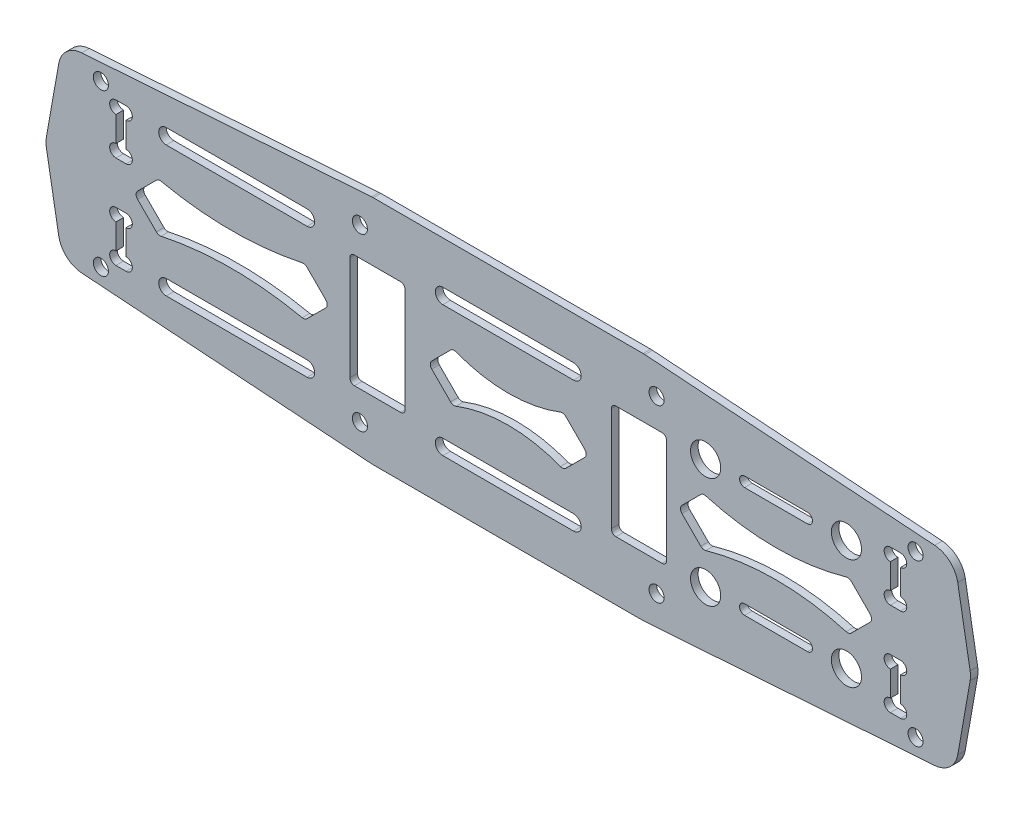
SolidWorks part; units mm, degrees
ref_plane "Front Plane" through (0, 0, 0) normal (0, 0, 1) x (1, 0, 0)
ref_plane "Top Plane" through (0, 0, 0) normal (0, 1, 0) x (1, 0, 0)
ref_plane "Right Plane" through (0, 0, 0) normal (1, 0, 0) x (0, 0, -1)
sketch "Sketch1" plane through (0, 0, 0) normal (0, 0, 1) x (1, 0, 0)
  line L0 (11.4571, 4.4571) -> (15.2071, 0.7071)
  line L1 (15.2071, -0.7071) -> (11.4571, -4.4571)
  line L2 (-11.4571, -4.4571) -> (-15.2071, -0.7071)
  line L3 (-15.2071, 0.7071) -> (-11.4571, 4.4571)
  line L4 (-84.8084, -18.9576) -> (-27.1742, -22.9878)
  line L5 (-26.8254, -23) -> (26.8254, -23)
  line L6 (27.1742, -22.9878) -> (84.8084, -18.9576)
  line L7 (89.3836, -14.8381) -> (91.8469, -0.8682)
  line L8 (91.8469, 0.8682) -> (89.3836, 14.8381)
  line L9 (84.8084, 18.9576) -> (27.1742, 22.9878)
  line L10 (26.8254, 23) -> (-26.8254, 23)
  line L11 (-27.1742, 22.9878) -> (-84.8084, 18.9576)
  line L12 (-89.3836, 14.8381) -> (-91.8469, 0.8682)
  line L13 (-91.8469, -0.8682) -> (-89.3836, -14.8381)
  line L14 (-40, 11.5) -> (-68, 11.5)
  line L15 (-68, 14.5) -> (-40, 14.5)
  line L16 (-40, -14.5) -> (-68, -14.5)
  line L17 (-68, -11.5) -> (-40, -11.5)
  line L18 (13, 11.5) -> (-13, 11.5)
  line L19 (-13, 14.5) -> (13, 14.5)
  line L20 (13, -14.5) -> (-13, -14.5)
  line L21 (-13, -11.5) -> (13, -11.5)
  line L22 (-21.4142, -11.25) -> (-30.5858, -11.25)
  line L23 (-31.5, -10.3358) -> (-31.5, 10.3358)
  line L24 (-30.5858, 11.25) -> (-21.4142, 11.25)
  line L25 (-20.5, 10.3358) -> (-20.5, -10.3358)
  line L26 (20.5, -10.3358) -> (20.5, 10.3358)
  line L27 (21.4142, 11.25) -> (30.5858, 11.25)
  line L28 (31.5, 10.3358) -> (31.5, -10.3358)
  line L29 (30.5858, -11.25) -> (21.4142, -11.25)
  line L30 (59.5, 10) -> (47, 10)
  line L31 (47, 12) -> (59.5, 12)
  line L32 (59.5, -12) -> (47, -12)
  line L33 (47, -10) -> (59.5, -10)
  line L34 (78, -6.75) -> (78, -11.75)
  line L35 (78, -14.25) -> (76, -14.25)
  line L36 (76, -11.75) -> (76, -6.75)
  line L37 (76, -4.25) -> (78, -4.25)
  line L38 (78, 4.25) -> (76, 4.25)
  line L39 (76, 6.75) -> (76, 11.75)
  line L40 (76, 14.25) -> (78, 14.25)
  line L41 (78, 11.75) -> (78, 6.75)
  line L42 (-76, 4.25) -> (-78, 4.25)
  line L43 (-78, 6.75) -> (-78, 11.75)
  line L44 (-78, 14.25) -> (-76, 14.25)
  line L45 (-76, 11.75) -> (-76, 6.75)
  line L46 (-76, -14.25) -> (-78, -14.25)
  line L47 (-78, -11.75) -> (-78, -6.75)
  line L48 (-78, -4.25) -> (-76, -4.25)
  line L49 (-76, -6.75) -> (-76, -11.75)
  line L50 (-40.0429, 4.4571) -> (-36.2929, 0.7071)
  line L51 (-36.2929, -0.7071) -> (-40.0429, -4.4571)
  line L52 (-69.9571, -4.4571) -> (-73.7071, -0.7071)
  line L53 (-73.7071, 0.7071) -> (-69.9571, 4.4571)
  line L54 (68.2071, 4.4571) -> (71.9571, 0.7071)
  line L55 (71.9571, -0.7071) -> (68.2071, -4.4571)
  line L56 (38.2929, -4.4571) -> (34.5429, -0.7071)
  line L57 (34.5429, 0.7071) -> (38.2929, 4.4571)
  arc A0 (-11.4571, 4.4571) -> (-10.3904, 4.6831) centre (-10.75, 3.75) cw
  arc A1 (-10.3904, 4.6831) -> (10.3904, 4.6831) centre (0, 31.6406) ccw
  arc A2 (10.3904, 4.6831) -> (11.4571, 4.4571) centre (10.75, 3.75) cw
  arc A3 (15.2071, 0.7071) -> (15.2071, -0.7071) centre (14.5, 0) cw
  arc A4 (11.4571, -4.4571) -> (10.3904, -4.6831) centre (10.75, -3.75) cw
  arc A5 (10.3904, -4.6831) -> (-10.3904, -4.6831) centre (0, -31.6406) ccw
  arc A6 (-10.3904, -4.6831) -> (-11.4571, -4.4571) centre (-10.75, -3.75) cw
  arc A7 (-15.2071, -0.7071) -> (-15.2071, 0.7071) centre (-14.5, 0) cw
  arc A8 (-27.1742, -22.9878) -> (-26.8254, -23) centre (-26.8254, -18) ccw
  arc A9 (26.8254, -23) -> (27.1742, -22.9878) centre (26.8254, -18) ccw
  arc A10 (84.8084, -18.9576) -> (89.3836, -14.8381) centre (84.4596, -13.9698) ccw
  arc A11 (91.8469, -0.8682) -> (91.8469, 0.8682) centre (86.9229, 0) ccw
  arc A12 (89.3836, 14.8381) -> (84.8084, 18.9576) centre (84.4596, 13.9698) ccw
  arc A13 (27.1742, 22.9878) -> (26.8254, 23) centre (26.8254, 18) ccw
  arc A14 (-26.8254, 23) -> (-27.1742, 22.9878) centre (-26.8254, 18) ccw
  arc A15 (-84.8084, 18.9576) -> (-89.3836, 14.8381) centre (-84.4596, 13.9698) ccw
  arc A16 (-91.8469, 0.8682) -> (-91.8469, -0.8682) centre (-86.9229, 0) ccw
  arc A17 (-89.3836, -14.8381) -> (-84.8084, -18.9576) centre (-84.4596, -13.9698) ccw
  arc A18 (-40, 14.5) -> (-40, 11.5) centre (-40, 13) cw
  arc A19 (-68, 11.5) -> (-68, 14.5) centre (-68, 13) cw
  arc A20 (-40, -11.5) -> (-40, -14.5) centre (-40, -13) cw
  arc A21 (-68, -14.5) -> (-68, -11.5) centre (-68, -13) cw
  arc A22 (13, 14.5) -> (13, 11.5) centre (13, 13) cw
  arc A23 (-13, 11.5) -> (-13, 14.5) centre (-13, 13) cw
  arc A24 (13, -11.5) -> (13, -14.5) centre (13, -13) cw
  arc A25 (-13, -14.5) -> (-13, -11.5) centre (-13, -13) cw
  arc A26 (-20.5, -10.3358) -> (-21.4142, -11.25) centre (-21.4142, -10.3358) cw
  arc A27 (-30.5858, -11.25) -> (-31.5, -10.3358) centre (-30.5858, -10.3358) cw
  arc A28 (-31.5, 10.3358) -> (-30.5858, 11.25) centre (-30.5858, 10.3358) cw
  arc A29 (-21.4142, 11.25) -> (-20.5, 10.3358) centre (-21.4142, 10.3358) cw
  arc A30 (21.4142, -11.25) -> (20.5, -10.3358) centre (21.4142, -10.3358) cw
  arc A31 (20.5, 10.3358) -> (21.4142, 11.25) centre (21.4142, 10.3358) cw
  arc A32 (30.5858, 11.25) -> (31.5, 10.3358) centre (30.5858, 10.3358) cw
  arc A33 (31.5, -10.3358) -> (30.5858, -11.25) centre (30.5858, -10.3358) cw
  arc A34 (59.5, 12) -> (59.5, 10) centre (59.5, 11) cw
  arc A35 (47, 10) -> (47, 12) centre (47, 11) cw
  arc A36 (59.5, -10) -> (59.5, -12) centre (59.5, -11) cw
  arc A37 (47, -12) -> (47, -10) centre (47, -11) cw
  arc A38 (78, -11.75) -> (78, -14.25) centre (78, -13) cw
  arc A39 (76, -14.25) -> (76, -11.75) centre (76, -13) cw
  arc A40 (76, -6.75) -> (76, -4.25) centre (76, -5.5) cw
  arc A41 (78, -4.25) -> (78, -6.75) centre (78, -5.5) cw
  arc A42 (78, 6.75) -> (78, 4.25) centre (78, 5.5) cw
  arc A43 (76, 4.25) -> (76, 6.75) centre (76, 5.5) cw
  arc A44 (76, 11.75) -> (76, 14.25) centre (76, 13) cw
  arc A45 (78, 14.25) -> (78, 11.75) centre (78, 13) cw
  arc A46 (-78, 4.25) -> (-78, 6.75) centre (-78, 5.5) cw
  arc A47 (-78, 11.75) -> (-78, 14.25) centre (-78, 13) cw
  arc A48 (-76, 14.25) -> (-76, 11.75) centre (-76, 13) cw
  arc A49 (-76, 6.75) -> (-76, 4.25) centre (-76, 5.5) cw
  arc A50 (-78, -14.25) -> (-78, -11.75) centre (-78, -13) cw
  arc A51 (-78, -6.75) -> (-78, -4.25) centre (-78, -5.5) cw
  arc A52 (-76, -4.25) -> (-76, -6.75) centre (-76, -5.5) cw
  arc A53 (-76, -11.75) -> (-76, -14.25) centre (-76, -13) cw
  circle A54 centre (39.25, 11) radius 3
  circle A55 centre (67.25, 11) radius 3
  circle A56 centre (39.25, -11) radius 3
  circle A57 centre (67.25, -11) radius 3
  circle A58 centre (81, 16) radius 1.5
  circle A59 centre (29.5, 17) radius 1.5
  circle A60 centre (-29.5, 17) radius 1.5
  circle A61 centre (-81, 16) radius 1.5
  circle A62 centre (-29.5, -17) radius 1.5
  circle A63 centre (29.5, -17) radius 1.5
  circle A64 centre (-81, -16) radius 1.5
  circle A65 centre (81, -16) radius 1.5
  arc A66 (-69.9571, 4.4571) -> (-69.0418, 4.7281) centre (-69.25, 3.75) cw
  arc A67 (-69.0418, 4.7281) -> (-40.9582, 4.7281) centre (-55, 70.6875) ccw
  arc A68 (-40.9582, 4.7281) -> (-40.0429, 4.4571) centre (-40.75, 3.75) cw
  arc A69 (-36.2929, 0.7071) -> (-36.2929, -0.7071) centre (-37, 0) cw
  arc A70 (-40.0429, -4.4571) -> (-40.9582, -4.7281) centre (-40.75, -3.75) cw
  arc A71 (-40.9582, -4.7281) -> (-69.0418, -4.7281) centre (-55, -70.6875) ccw
  arc A72 (-69.0418, -4.7281) -> (-69.9571, -4.4571) centre (-69.25, -3.75) cw
  arc A73 (-73.7071, -0.7071) -> (-73.7071, 0.7071) centre (-73, 0) cw
  arc A74 (71.9571, 0.7071) -> (71.9571, -0.7071) centre (71.25, 0) cw
  arc A75 (68.2071, -4.4571) -> (67.2247, -4.7114) centre (67.5, -3.75) cw
  arc A76 (67.2247, -4.7114) -> (39.2753, -4.7114) centre (53.25, -53.5156) ccw
  arc A77 (39.2753, -4.7114) -> (38.2929, -4.4571) centre (39, -3.75) cw
  arc A78 (34.5429, -0.7071) -> (34.5429, 0.7071) centre (35.25, 0) cw
  arc A79 (38.2929, 4.4571) -> (39.2753, 4.7114) centre (39, 3.75) cw
  arc A80 (39.2753, 4.7114) -> (67.2247, 4.7114) centre (53.25, 53.5156) ccw
  arc A81 (67.2247, 4.7114) -> (68.2071, 4.4571) centre (67.5, 3.75) cw
extrude "top-plate" add sketch "Sketch1" against normal blind 1.5
